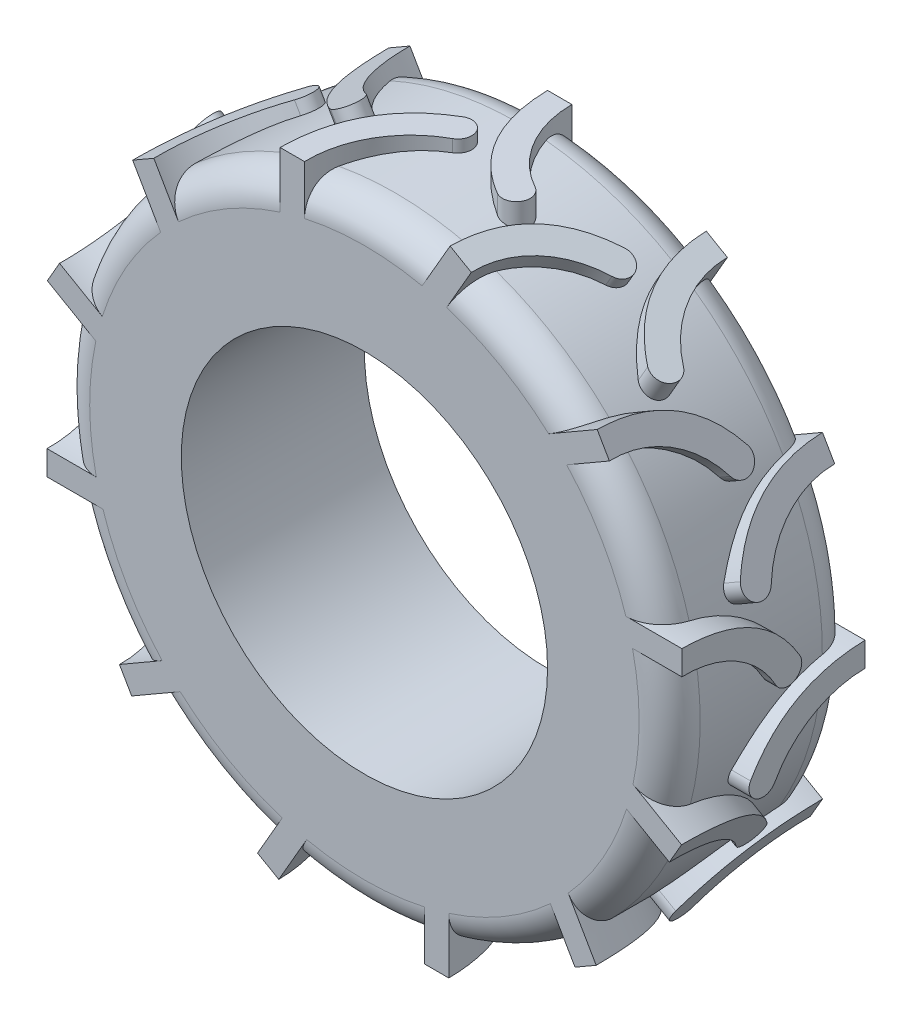
SolidWorks part; units mm, degrees
ref_plane "Alzado" through (0, 0, 0) normal (0, 0, 1) x (1, 0, 0)
ref_plane "Planta" through (0, 0, 0) normal (0, 1, 0) x (1, 0, 0)
ref_plane "Vista lateral" through (0, 0, 0) normal (1, 0, 0) x (0, 0, -1)
sketch "Sketch2" plane through (0, 0, 0) normal (0, 0, 1) x (1, 0, 0)
  circle A0 centre (0, 0) radius 50
  circle A1 centre (0, 0) radius 30
  dimension "D1" = 100
  dimension "D2" = 60
extrude "Boss-Extrude1" add sketch "Sketch2" along normal blind 30
fillet "Fillet1" radius 5 2 edges at (50, 0, 0) (50, 0, 30)
ref_plane "Plane2" through (52, 0, 0) normal (1, 0, 0) x (0, 0, -1)
sketch "Sketch7" plane through (52, 0, 0) normal (1, 0, 0) x (0, 0, -1)
  line L0 (-15, 50) -> (-15, -49950) construction
  line L1 (-5, 50) -> (-25, 50) construction
  line L2 (0, 0.0105) -> (0, -3.9895)
  line L3 (0, -45) -> (0, 45) construction
  line L5 (-30, 13.8163) -> (-30, 9.8095)
  line L6 (-30, 45) -> (-30, -45) construction
  arc A0 (0, -3.9895) -> (-14.7514, -12.7139) centre (0, -20.8226) ccw
  arc A1 (-14.7514, -12.7139) -> (-18.7514, -10.5778) centre (-16.7384, -11.6217) cw
  arc A4 (-14.6222, 0.9681) -> (-10.6222, 3.1046) centre (-12.6311, 2.0529) ccw
  arc A5 (-30, 9.8095) -> (-14.6222, 0.9681) centre (-29.5191, -7.148) cw
  spline S0 degree 2 poles (-18.7514, -10.5778) (-12.8273, -0.2816) (0, 0.0105) knots 0 0 0 1 1 1
  spline S1 degree 2 poles (-10.6222, 3.1046) (-16.7451, 13.6581) (-30, 13.8163) knots 0 0 0 1 1 1
  point P4 (-15, 50)
  dimension "D1" = 4
  dimension "D2" = 4
extrude "Boss-Extrude5" add sketch "Sketch7" against normal up to surface (23.9267 mm away)
pattern_circular "CirPattern1" count 12 over 360 about axis through (0, 0, 30) along (0, 0, -1) of "Boss-Extrude5"
